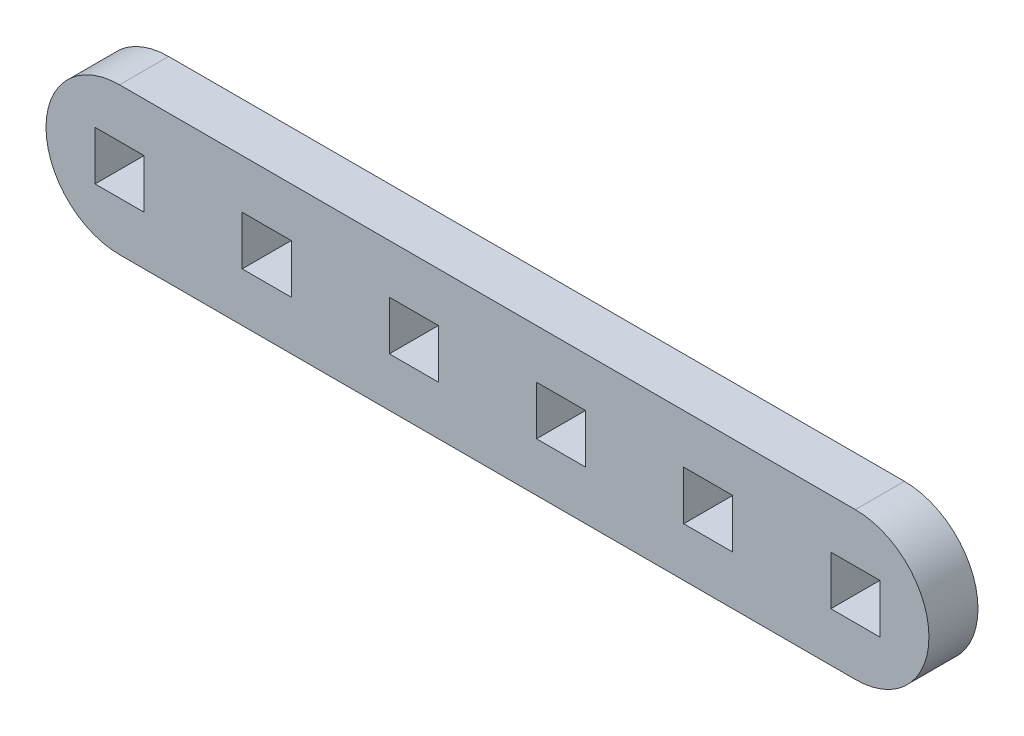
SolidWorks part; units mm, degrees
ref_plane "Alzado" through (0, 0, 0) normal (0, 0, 1) x (1, 0, 0)
ref_plane "Planta" through (0, 0, 0) normal (0, 1, 0) x (1, 0, 0)
ref_plane "Vista lateral" through (0, 0, 0) normal (1, 0, 0) x (0, 0, -1)
sketch "Model" plane through (0, 0, 0) normal (0, 0, 1) x (1, 0, 0)
  line L0 (10.6812, 295.1365) -> (10.6812, 292.1365)
  line L1 (13.6812, 295.1365) -> (10.6812, 295.1365)
  line L2 (13.6812, 292.1365) -> (13.6812, 295.1365)
  line L3 (10.6812, 292.1365) -> (13.6812, 292.1365)
  line L4 (19.6812, 295.1365) -> (19.6812, 292.1365)
  line L5 (22.6812, 295.1365) -> (19.6812, 295.1365)
  line L6 (22.6812, 292.1365) -> (22.6812, 295.1365)
  line L7 (19.6812, 292.1365) -> (22.6812, 292.1365)
  line L8 (28.6812, 295.1365) -> (28.6812, 292.1365)
  line L9 (31.6812, 295.1365) -> (28.6812, 295.1365)
  line L10 (31.6812, 292.1365) -> (31.6812, 295.1365)
  line L11 (28.6812, 292.1365) -> (31.6812, 292.1365)
  line L12 (37.6812, 295.1365) -> (37.6812, 292.1365)
  line L13 (40.6812, 295.1365) -> (37.6812, 295.1365)
  line L14 (40.6812, 292.1365) -> (40.6812, 295.1365)
  line L15 (37.6812, 292.1365) -> (40.6812, 292.1365)
  line L16 (55.6812, 295.1365) -> (55.6812, 292.1365)
  line L17 (58.6812, 295.1365) -> (55.6812, 295.1365)
  line L18 (58.6812, 292.1365) -> (58.6812, 295.1365)
  line L19 (55.6812, 292.1365) -> (58.6812, 292.1365)
  line L20 (46.6812, 295.1365) -> (46.6812, 292.1365)
  line L21 (49.6812, 295.1365) -> (46.6812, 295.1365)
  line L22 (49.6812, 292.1365) -> (49.6812, 295.1365)
  line L23 (46.6812, 292.1365) -> (49.6812, 292.1365)
  line L24 (12.1812, 298.1365) -> (57.1812, 298.1365)
  line L25 (12.1812, 289.1365) -> (57.1812, 289.1365)
  arc A0 (12.1812, 298.1365) -> (12.1812, 289.1365) centre (12.1812, 293.6365) ccw
  arc A1 (57.1812, 289.1365) -> (57.1812, 298.1365) centre (57.1812, 293.6365) ccw
extrude "Saliente-Extruir1" add sketch "Model" along normal blind 3
